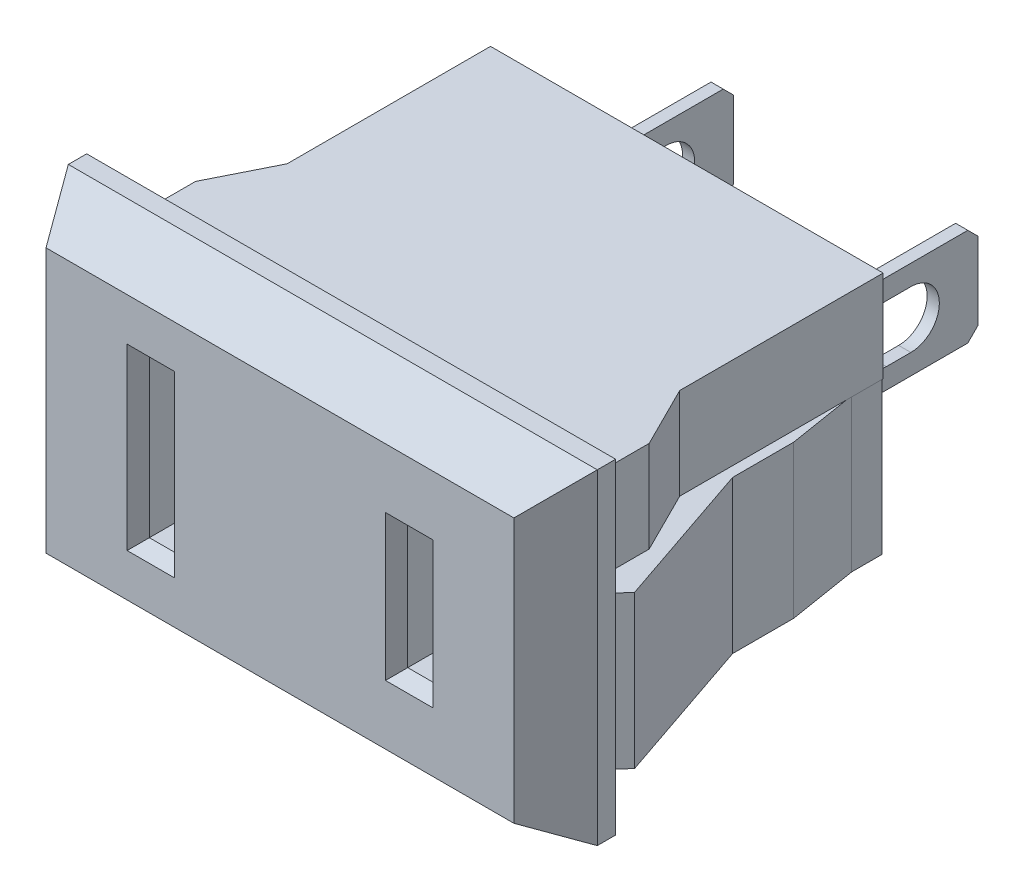
SolidWorks part; units mm, degrees
ref_plane "Front Plane" through (0, 0, 0) normal (0, 0, 1) x (1, 0, 0)
ref_plane "Top Plane" through (0, 0, 0) normal (0, 1, 0) x (1, 0, 0)
ref_plane "Right Plane" through (0, 0, 0) normal (1, 0, 0) x (0, 0, -1)
ref_plane "Plane1" through (0, -8, 0) normal (0, -1, 0) x (1, 0, 0)
sketch "Sketch1" plane through (0, -8, 0) normal (0, -1, 0) x (1, 0, 0)
  line L0 (12.8033, -0.8) -> (9.65, -0.8)
  line L1 (9.65, -0.8) -> (9.65, -14.6909)
  line L2 (9.65, -14.6909) -> (10.15, -11.6)
  line L3 (10.15, -11.6) -> (10.15, -8.6)
  line L4 (10.15, -8.6) -> (12.8033, -0.8)
extrude "Boss-Extrude1" add sketch "Sketch1" against normal blind 16
sketch "Sketch2" plane through (0, 0, -0.8) normal (0, 0, 1) x (1, 0, 0)
  line L0 (9.65, 8) -> (11.15, 8)
  line L1 (11.15, 8) -> (11.15, -8)
  line L2 (11.15, -8) -> (9.65, -8)
  line L3 (9.65, -8) -> (9.65, 8)
extrude "Boss-Extrude2" add sketch "Sketch2" along normal blind 0.8
sketch "Sketch3" plane through (9.65, 0, 0) normal (-1, 0, 0) x (0, 0, 1)
  line L0 (0, -8) -> (-16.5, -8)
  line L1 (-16.5, -8) -> (-16.5, 8)
  line L2 (-16.5, 8) -> (0, 8)
  line L3 (0, 8) -> (0, -8)
extrude "Boss-Extrude3" add sketch "Sketch3" along normal blind 20.8
sketch "Sketch4" plane through (0, 0, 0) normal (0, 0, 1) x (1, 0, 0)
  line L0 (-11.15, 8) -> (13, 8)
  line L1 (13, 8) -> (13, -8)
  line L2 (13, -8) -> (-11.15, -8)
  line L3 (-11.15, -8) -> (-11.15, 8)
extrude "Boss-Extrude4" add sketch "Sketch4" along normal blind 3.5
sketch "Sketch5" plane through (0, 8, 0) normal (0, 1, 0) x (-1, 0, 0)
  line L0 (-9.65, -14.6909) -> (-9.65, -6.5)
  line L1 (-9.65, -6.5) -> (-11.15, -3.5)
  line L2 (-11.15, -3.5) -> (-11.15, -0.8)
  line L3 (-11.15, -0.8) -> (-12.8033, -0.8)
  line L4 (-12.8033, -0.8) -> (-10.15, -8.6)
  line L5 (-10.15, -8.6) -> (-10.15, -11.6)
  line L6 (-10.15, -11.6) -> (-9.65, -14.6909)
extrude "Cut-Extrude1" cut sketch "Sketch5" against normal blind 6.5
sketch "Sketch6" plane through (0, 8, 0) normal (0, 1, 0) x (-1, 0, 0)
  line L0 (-11.15, 0) -> (-11.15, -3.5)
  line L1 (-11.15, -3.5) -> (-9.65, -6.5)
  line L2 (-9.65, -6.5) -> (-9.65, -16.5)
  line L3 (-9.65, -16.5) -> (11.15, -16.5)
  line L4 (11.15, -16.5) -> (11.15, 0)
  line L5 (11.15, 0) -> (-11.15, 0)
extrude "Cut-Extrude2" cut sketch "Sketch6" against normal blind 2
sketch "Sketch7" plane through (0, -8, 0) normal (0, -1, 0) x (1, 0, 0)
  line L0 (11.15, -0.8) -> (11.15, 0)
  line L1 (11.15, 0) -> (-11.15, 0)
  line L2 (-11.15, 0) -> (-11.15, -16.5)
  line L3 (-11.15, -16.5) -> (9.65, -16.5)
  line L4 (9.65, -16.5) -> (9.65, -14.6909)
  line L5 (9.65, -14.6909) -> (10.15, -11.6)
  line L6 (10.15, -11.6) -> (10.15, -8.6)
  line L7 (10.15, -8.6) -> (12.8033, -0.8)
  line L8 (12.8033, -0.8) -> (11.15, -0.8)
extrude "Cut-Extrude3" cut sketch "Sketch7" against normal blind 2
sketch "Sketch8" plane through (0, -6, 0) normal (0, -1, 0) x (1, 0, 0)
  line L0 (1.5, -7) -> (1.5, 0)
  line L1 (1.5, 0) -> (-1.5, 0)
  line L2 (-1.5, 0) -> (-1.5, -7)
  line L3 (-1.5, -7) -> (1.5, -7)
extrude "Cut-Extrude4" cut sketch "Sketch8" against normal blind 2.5
sketch "Sketch9" plane through (0, -6, 0) normal (0, -1, 0) x (1, 0, 0)
  line L0 (-1.5, -7) -> (-1.5, -16.5)
  line L1 (-1.5, -16.5) -> (7, -16.5)
  line L2 (7, -16.5) -> (7, 0)
  line L3 (7, 0) -> (1.5, 0)
  line L4 (1.5, 0) -> (1.5, -7)
  line L5 (1.5, -7) -> (-1.5, -7)
extrude "Cut-Extrude5" cut sketch "Sketch9" against normal blind 1
sketch "Sketch10" plane through (-11.15, 0, 0) normal (-1, 0, 0) x (0, 0, 1)
  line L0 (3.5, -8) -> (0, -8)
  line L1 (0, -8) -> (0, 8)
  line L2 (0, 8) -> (3.5, 8)
  line L3 (3.5, 8) -> (3.5, -8)
extrude "Boss-Extrude5" add sketch "Sketch10" along normal blind 1.85
sketch "Sketch11" plane through (0, -6, 0) normal (0, -1, 0) x (1, 0, 0)
  line L0 (-11.15, 0) -> (-11.15, -16.5)
  line L1 (-11.15, -16.5) -> (-9.15, -16.5)
  line L2 (-9.15, -16.5) -> (-9.15, 0)
  line L3 (-9.15, 0) -> (-11.15, 0)
extrude "Cut-Extrude6" cut sketch "Sketch11" against normal blind 9.8
sketch "Sketch12" plane through (-1.5, 0, 0) normal (1, 0, 0) x (0, 0, -1)
  line L0 (16.5, -6) -> (16.5, -5)
  line L1 (16.5, -5) -> (0, -5)
  line L2 (0, -5) -> (0, -6)
  line L3 (0, -6) -> (16.5, -6)
extrude "Cut-Extrude7" cut sketch "Sketch12" against normal blind 5.5
ref_plane "Plane2" through (0, -6, 0) normal (0, -1, 0) x (1, 0, 0)
sketch "Sketch13" plane through (0, -6, 0) normal (0, -1, 0) x (1, 0, 0)
  line L0 (-9.15, -6.567) -> (-10.6953, -0.8)
  line L1 (-10.6953, -0.8) -> (-12.8033, -0.8)
  line L2 (-12.8033, -0.8) -> (-10.15, -8.6)
  line L3 (-10.15, -8.6) -> (-10.15, -11.6)
  line L4 (-10.15, -11.6) -> (-9.6, -15)
  line L5 (-9.6, -15) -> (-9.6, -16.5)
  line L6 (-9.6, -16.5) -> (-9.15, -16.5)
  line L7 (-9.15, -16.5) -> (-9.15, -6.567)
extrude "Boss-Extrude6" add sketch "Sketch13" against normal blind 7.5
sketch "Sketch14" plane through (0, -6, 0) normal (0, -1, 0) x (1, 0, 0)
  line L0 (-9.15, 0) -> (-9.15, -6.567)
  line L1 (-9.15, -6.567) -> (-8.9, -7.5)
  line L2 (-8.9, -7.5) -> (-8.9, -9.5)
  line L3 (-8, -9.5) -> (-8, 0)
  line L4 (-8, 0) -> (-9.15, 0)
  arc A0 (-8.9, -9.5) -> (-8, -9.5) centre (-8.45, -9.5) ccw
extrude "Cut-Extrude8" cut sketch "Sketch14" against normal blind 7.5
sketch "Sketch15" plane through (0, -6, 0) normal (0, -1, 0) x (1, 0, 0)
  line L0 (8.9, -9.5) -> (8.9, -7.5)
  line L1 (8.9, -7.5) -> (10.6953, -0.8)
  line L2 (10.6953, -0.8) -> (11.15, -0.8)
  line L3 (11.15, -0.8) -> (11.15, 0)
  line L4 (11.15, 0) -> (8, 0)
  line L5 (8, 0) -> (8, -9.5)
  arc A0 (8, -9.5) -> (8.9, -9.5) centre (8.45, -9.5) ccw
extrude "Cut-Extrude9" cut sketch "Sketch15" against normal blind 7.5
sketch "Sketch16" plane through (0, 0, -16.5) normal (0, 0, -1) x (-1, 0, 0)
  line L0 (-6.312, 3.5) -> (-5.712, 3.5)
  line L1 (-5.712, 3.5) -> (-5.712, -3.5)
  line L2 (-5.712, -3.5) -> (-6.312, -3.5)
  line L3 (-6.312, -3.5) -> (-6.312, 3.5)
extrude "Boss-Extrude7" add sketch "Sketch16" along normal blind 8
sketch "Sketch17" plane through (6.312, 0, 0) normal (1, 0, 0) x (0, 0, -1)
  line L0 (24.5, 3.5) -> (18, 3.5)
  line L1 (18, 3.5) -> (18, 2.4)
  line L2 (18, 2.4) -> (24.5, 2.4)
  line L3 (24.5, 2.4) -> (24.5, 3.5)
extrude "Cut-Extrude10" cut sketch "Sketch17" against normal through all
sketch "Sketch18" plane through (6.312, 0, 0) normal (1, 0, 0) x (0, 0, -1)
  line L0 (24.5, -2.4) -> (18, -2.4)
  line L1 (18, -2.4) -> (18, -3.5)
  line L2 (18, -3.5) -> (24.5, -3.5)
  line L3 (24.5, -3.5) -> (24.5, -2.4)
extrude "Cut-Extrude11" cut sketch "Sketch18" against normal through all
sketch "Sketch19" plane through (0, 0, -16.5) normal (0, 0, -1) x (-1, 0, 0)
  line L0 (5.712, 3.5) -> (6.312, 3.5)
  line L1 (6.312, 3.5) -> (6.312, -3.5)
  line L2 (6.312, -3.5) -> (5.712, -3.5)
  line L3 (5.712, -3.5) -> (5.712, 3.5)
extrude "Boss-Extrude8" add sketch "Sketch19" along normal blind 8
sketch "Sketch20" plane through (-5.712, 0, 0) normal (1, 0, 0) x (0, 0, -1)
  line L0 (24.5, 3.5) -> (18, 3.5)
  line L1 (18, 3.5) -> (18, 2.4)
  line L2 (18, 2.4) -> (24.5, 2.4)
  line L3 (24.5, 2.4) -> (24.5, 3.5)
extrude "Cut-Extrude12" cut sketch "Sketch20" against normal through all
sketch "Sketch21" plane through (-5.712, 0, 0) normal (1, 0, 0) x (0, 0, -1)
  line L0 (24.5, -2.4) -> (18, -2.4)
  line L1 (18, -2.4) -> (18, -3.5)
  line L2 (18, -3.5) -> (24.5, -3.5)
  line L3 (24.5, -3.5) -> (24.5, -2.4)
extrude "Cut-Extrude13" cut sketch "Sketch21" against normal through all
sketch "Sketch22" plane through (0, 6, 0) normal (0, 1, 0) x (-1, 0, 0)
  line L0 (11.15, -3.5) -> (9.65, -6.5)
  line L1 (9.65, -6.5) -> (9.65, -16.5)
  line L2 (9.65, -16.5) -> (11.15, -16.5)
  line L3 (11.15, -16.5) -> (11.15, -3.5)
extrude "Cut-Extrude14" cut sketch "Sketch22" against normal up to next
sketch "Sketch23" plane through (6.312, 0, 0) normal (1, 0, 0) x (0, 0, -1)
  line L0 (20, -1.4) -> (21.2, -1.4)
  line L1 (21.2, 1.4) -> (20, 1.4)
  arc A0 (21.2, -1.4) -> (21.2, 1.4) centre (21.2, 0) ccw
  arc A1 (20, 1.4) -> (20, -1.4) centre (20, 0) ccw
extrude "Cut-Extrude15" cut sketch "Sketch23" against normal up to next
sketch "Sketch24" plane through (-5.712, 0, 0) normal (1, 0, 0) x (0, 0, -1)
  line L0 (20, -1.4) -> (21.2, -1.4)
  line L1 (21.2, 1.4) -> (20, 1.4)
  arc A0 (21.2, -1.4) -> (21.2, 1.4) centre (21.2, 0) ccw
  arc A1 (20, 1.4) -> (20, -1.4) centre (20, 0) ccw
extrude "Cut-Extrude16" cut sketch "Sketch24" against normal through all
sketch "Sketch25" plane through (0, -6, 0) normal (0, -1, 0) x (1, 0, 0)
  line L0 (9.6, -15) -> (9.6, -16.5)
  line L1 (9.6, -16.5) -> (9.65, -16.5)
  line L2 (9.65, -16.5) -> (9.65, -14.6909)
  line L3 (9.65, -14.6909) -> (9.6, -15)
extrude "Cut-Extrude17" cut sketch "Sketch25" against normal blind 7.5
sketch "Sketch26" plane through (0, -5, 0) normal (0, -1, 0) x (1, 0, 0)
  line L0 (2.2, -13.5) -> (3.191, -13.5)
  line L1 (3.191, -13.5) -> (3.191, -8.5)
  line L2 (3.191, -8.5) -> (1, -8.5)
  line L3 (1, -8.5) -> (1, -12.7)
  line L4 (1, -12.7) -> (2.2, -12.7)
  line L5 (2.2, -12.7) -> (2.2, -13.5)
extrude "Cut-Extrude18" cut sketch "Sketch26" against normal blind 1.5
sketch "Sketch27" plane through (0, -5, 0) normal (0, -1, 0) x (1, 0, 0)
  line L0 (-2.2, -13.5) -> (-2.2, -12.7)
  line L1 (-2.2, -12.7) -> (-1, -12.7)
  line L2 (-1, -12.7) -> (-1, -8.5)
  line L3 (-1, -8.5) -> (-3.191, -8.5)
  line L4 (-3.191, -8.5) -> (-3.191, -13.5)
  line L5 (-3.191, -13.5) -> (-2.2, -13.5)
extrude "Cut-Extrude19" cut sketch "Sketch27" against normal blind 1.5
sketch "Sketch28" plane through (0, 0, 3.5) normal (0, 0, 1) x (1, 0, 0)
  line L0 (-5.588, -3.994) -> (-5.588, 3.994)
  line L1 (-5.588, 3.994) -> (-7.112, 3.994)
  line L2 (-7.112, 3.994) -> (-7.112, -3.994)
  line L3 (-7.112, -3.994) -> (-5.588, -3.994)
extrude "Cut-Extrude20" cut sketch "Sketch28" against normal blind 18
sketch "Sketch29" plane through (0, 0, 3.5) normal (0, 0, 1) x (1, 0, 0)
  line L0 (7.112, -3.175) -> (7.112, 3.175)
  line L1 (7.112, 3.175) -> (5.588, 3.175)
  line L2 (5.588, 3.175) -> (5.588, -3.175)
  line L3 (5.588, -3.175) -> (7.112, -3.175)
extrude "Cut-Extrude21" cut sketch "Sketch29" against normal blind 18
chamfer "Chamfer1" distance 0.5 angle 45 4 edges at (-6.012, 2.4, -24.5) (6.012, 2.4, -24.5) (-6.012, -2.4, -24.5) (6.012, -2.4, -24.5)
chamfer "Chamfer2" distance 0.5281 angle 60 1 edges at (-12.8033, -2.25, -0.8)
chamfer "Chamfer3" distance 0.4 angle 60 8 edges at (-5.588, 0, 3.5) (-6.35, -3.994, 3.5) (-6.35, 3.994, 3.5) (-7.112, 0, 3.5) (6.35, 3.175, 3.5) (7.112, 0, 3.5) (5.588, 0, 3.5) (6.35, -3.175, 3.5)
chamfer "Chamfer4" distance 0.608 angle 48.786 1 edges at (12.8033, -2.25, -0.8)
chamfer "Chamfer5" distance 1.5 angle 60 4 edges at (13, 0, 3.5) (0, 8, 3.5) (0, -8, 3.5) (-13, 0, 3.5)
sketch3d "3DSketch1"
  spline S0 degree 1 poles (11.25, -6.15, -0.8) (11.25, 6.15, -0.8) knots 0 0 1 1
  spline S1 degree 1 poles (11.25, 6.15, -0.8) (-11.25, 6.15, -0.8) knots 0 0 1 1
  spline S2 degree 1 poles (-11.25, 6.15, -0.8) (-11.25, 3.65, -0.8) knots 0 0 1 1
  spline S3 degree 1 poles (-11.25, 3.65, -0.8) (-9.25, 3.65, -0.8) knots 0 0 1 1
  spline S4 degree 1 poles (-9.25, 3.65, -0.8) (-9.25, 1.65, -0.8) knots 0 0 1 1
  spline S5 degree 1 poles (-9.25, 1.65, -0.8) (-11.25, 1.65, -0.8) knots 0 0 1 1
  spline S6 degree 1 poles (-11.25, 1.65, -0.8) (-11.25, -6.15, -0.8) knots 0 0 1 1
  spline S7 degree 1 poles (-11.25, -6.15, -0.8) (11.25, -6.15, -0.8) knots 0 0 1 1
